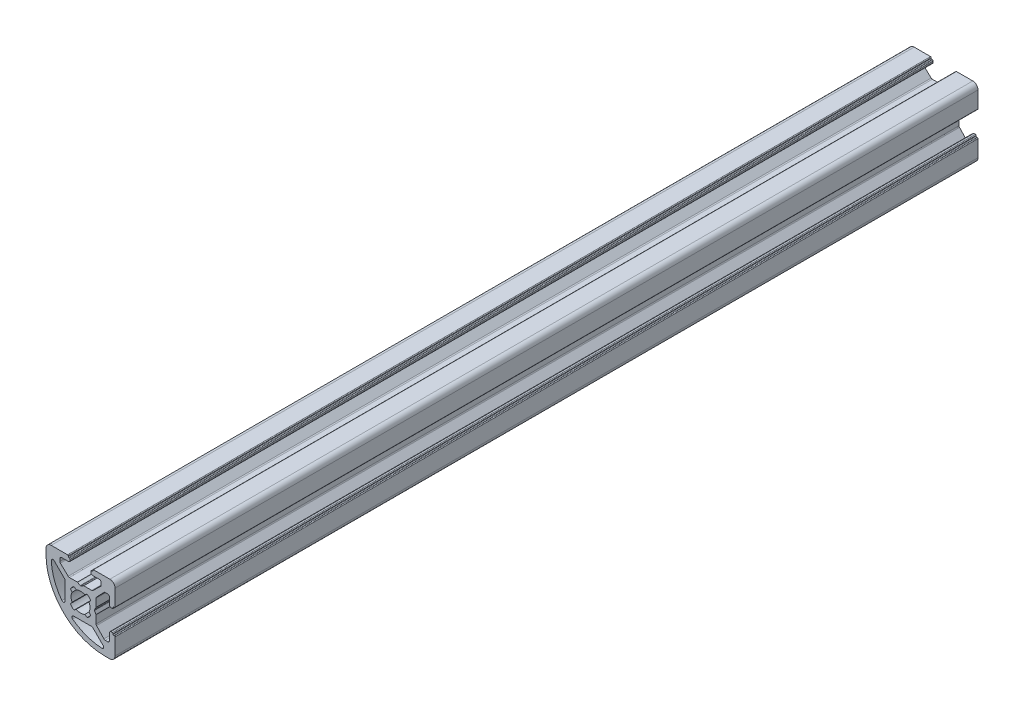
SolidWorks part; units mm, degrees
ref_plane "Front Plane" through (0, 0, 0) normal (0, 0, 1) x (1, 0, 0)
ref_plane "Top Plane" through (0, 0, 0) normal (0, 1, 0) x (1, 0, 0)
ref_plane "Right Plane" through (0, 0, 0) normal (1, 0, 0) x (0, 0, -1)
sketch "Sketch1" plane through (0, 0, 0) normal (0, 0, 1) x (1, 0, 0)
  line L0 (1.2582, 2.4453) -> (1.8871, 2.9477)
  line L1 (1.2582, -2.4453) -> (1.8871, -2.9477)
  line L2 (3.2322, 4.5654) -> (0.9536, 4.5654)
  line L3 (3.2322, -4.5) -> (-2, -4.5)
  line L4 (-1.2582, -2.4453) -> (-1.8871, -2.9477)
  line L5 (-4.6464, 3.5858) -> (-7.6257, 6.565)
  line L6 (-10, 7) -> (-10, 8.5)
  line L7 (-2.4453, -1.2582) -> (-2.9477, -1.8871)
  line L8 (-2.4453, 1.2582) -> (-2.9477, 1.8871)
  line L9 (-4.5, 3.2322) -> (-4.5, -2)
  line L10 (-1.2582, 2.4453) -> (-1.8871, 2.9477)
  line L11 (-3.2322, 4.5654) -> (-0.9536, 4.5654)
  line L12 (-3.2, 9.45) -> (-3.35, 9.45)
  line L13 (-3, 8.9321) -> (-3, 9.25)
  line L14 (-3.4918, 8.4403) -> (-5.5082, 8.4403)
  line L15 (-3.5763, 4.7027) -> (-5.8441, 6.8535)
  line L16 (-6, 7.2162) -> (-6, 7.9485)
  line L17 (-0.8536, 4.5387) -> (-0.1, 4.1036)
  line L18 (0.8536, 4.5387) -> (0.1, 4.1036)
  line L19 (-3.75, 10) -> (-8.5, 10)
  line L20 (-3.55, 9.65) -> (-3.55, 9.8)
  line L21 (4.5, -3.2322) -> (4.5, -0.9536)
  line L22 (9.65, -3.55) -> (9.8, -3.55)
  line L23 (7, -10) -> (8.5, -10)
  line L24 (4.6372, -3.5763) -> (6.788, -5.8441)
  line L25 (3.5858, -4.6464) -> (6.565, -7.6257)
  line L26 (8.3748, -3.4918) -> (8.3748, -5.5082)
  line L27 (9.45, -3.2) -> (9.45, -3.35)
  line L28 (8.8666, -3) -> (9.25, -3)
  line L29 (7.1508, -6) -> (7.883, -6)
  line L30 (10, -3.75) -> (10, -8.5)
  line L31 (9.65, 3.55) -> (9.8, 3.55)
  line L32 (8.3748, 3.4918) -> (8.3748, 5.5082)
  line L33 (4.6372, 3.5763) -> (6.788, 5.8441)
  line L34 (2.4453, 1.2582) -> (2.9477, 1.8871)
  line L35 (2.4453, -1.2582) -> (2.9477, -1.8871)
  line L36 (4.5, 3.2322) -> (4.5, 0.9536)
  line L37 (4.4732, 0.8536) -> (4.0381, 0.1)
  line L38 (4.4732, -0.8536) -> (4.0381, -0.1)
  line L39 (9.45, 3.2) -> (9.45, 3.35)
  line L40 (8.8666, 3) -> (9.25, 3)
  line L42 (3.5763, 4.7027) -> (5.8441, 6.8535)
  line L43 (3.4918, 8.4403) -> (5.5082, 8.4403)
  line L44 (3.2, 9.45) -> (3.35, 9.45)
  line L45 (3, 8.9321) -> (3, 9.25)
  line L46 (6, 7.2162) -> (6, 7.9485)
  line L47 (7.1508, 6) -> (7.883, 6)
  line L48 (10, 3.75) -> (10, 8.5)
  line L49 (3.75, 10) -> (8.5, 10)
  line L50 (3.55, 9.65) -> (3.55, 9.8)
  line L51 (0, 13.6082) -> (0, -13.4183) construction
  line L52 (-13.988, 0) -> (15.7602, 0) construction
  arc A0 (-2.3, -5.4) -> (6.1852, -8.4786) centre (7, 7) ccw
  arc A1 (-10, 7) -> (7, -10) centre (7, 7) ccw
  arc A2 (-3.55, 9.65) -> (-3.35, 9.45) centre (-3.35, 9.65) ccw
  arc A3 (-8.5, 10) -> (-10, 8.5) centre (-8.5, 8.5) ccw
  arc A4 (-5.4, -2.3) -> (-4.5, -2) centre (-5, -2) ccw
  arc A5 (-8.4786, 6.1852) -> (-5.4, -2.3) centre (7, 7) ccw
  arc A6 (-2.9477, -1.8871) -> (-1.8871, -2.9477) centre (0, 0) ccw
  arc A7 (-2, -4.5) -> (-2.3, -5.4) centre (-2, -5) ccw
  arc A8 (-1.2582, -2.4453) -> (1.2582, -2.4453) centre (0, 0) ccw
  arc A9 (-7.6257, 6.565) -> (-8.4786, 6.1852) centre (-7.9793, 6.2115) ccw
  arc A10 (-1.8871, 2.9477) -> (-2.9477, 1.8871) centre (0, 0) ccw
  arc A11 (-4.5, 3.2322) -> (-4.6464, 3.5858) centre (-5, 3.2322) ccw
  arc A12 (1.2582, 2.4453) -> (-1.2582, 2.4453) centre (0, 0) ccw
  arc A13 (-2.4453, 1.2582) -> (-2.4453, -1.2582) centre (0, 0) ccw
  arc A14 (-3, 9.25) -> (-3.2, 9.45) centre (-3.2, 9.25) ccw
  arc A15 (-3.4918, 8.4403) -> (-3, 8.9321) centre (-3.4918, 8.9321) ccw
  arc A16 (-3.5763, 4.7027) -> (-3.2322, 4.5654) centre (-3.2322, 5.0654) ccw
  arc A17 (-6, 7.2162) -> (-5.8441, 6.8535) centre (-5.5, 7.2162) ccw
  arc A18 (-5.5082, 8.4403) -> (-6, 7.9485) centre (-5.5082, 7.9485) ccw
  arc A19 (-0.1, 4.1036) -> (0.1, 4.1036) centre (0, 4.2768) ccw
  arc A20 (0.9536, 4.5654) -> (0.8536, 4.5387) centre (0.9536, 4.3654) ccw
  arc A21 (-0.8536, 4.5387) -> (-0.9536, 4.5654) centre (-0.9536, 4.3654) ccw
  arc A22 (-3.55, 9.8) -> (-3.75, 10) centre (-3.75, 9.8) ccw
  arc A23 (3.35, 9.45) -> (3.55, 9.65) centre (3.35, 9.65) ccw
  arc A24 (10, 8.5) -> (8.5, 10) centre (8.5, 8.5) ccw
  arc A25 (1.8871, -2.9477) -> (2.9477, -1.8871) centre (0, 0) ccw
  arc A26 (8.5, -10) -> (10, -8.5) centre (8.5, -8.5) ccw
  arc A27 (6.1852, -8.4786) -> (6.565, -7.6257) centre (6.2115, -7.9793) ccw
  arc A28 (4.5, -3.2322) -> (4.6372, -3.5763) centre (5, -3.2322) ccw
  arc A29 (3.5858, -4.6464) -> (3.2322, -4.5) centre (3.2322, -5) ccw
  arc A30 (9.45, -3.2) -> (9.25, -3) centre (9.25, -3.2) ccw
  arc A31 (9.45, -3.35) -> (9.65, -3.55) centre (9.65, -3.35) ccw
  arc A32 (8.8666, -3) -> (8.3748, -3.4918) centre (8.8666, -3.4918) ccw
  arc A33 (6.788, -5.8441) -> (7.1508, -6) centre (7.1508, -5.5) ccw
  arc A34 (7.883, -6) -> (8.3748, -5.5082) centre (7.883, -5.5082) ccw
  arc A35 (10, -3.75) -> (9.8, -3.55) centre (9.8, -3.75) ccw
  arc A36 (2.4453, -1.2582) -> (2.4453, 1.2582) centre (0, 0) ccw
  arc A37 (2.9477, 1.8871) -> (1.8871, 2.9477) centre (0, 0) ccw
  arc A38 (4.0381, 0.1) -> (4.0381, -0.1) centre (4.2113, 0) ccw
  arc A39 (4.5, -0.9536) -> (4.4732, -0.8536) centre (4.3, -0.9536) ccw
  arc A40 (4.4732, 0.8536) -> (4.5, 0.9536) centre (4.3, 0.9536) ccw
  arc A41 (4.6372, 3.5763) -> (4.5, 3.2322) centre (5, 3.2322) ccw
  arc A42 (9.65, 3.55) -> (9.45, 3.35) centre (9.65, 3.35) ccw
  arc A43 (9.25, 3) -> (9.45, 3.2) centre (9.25, 3.2) ccw
  arc A44 (8.3748, 3.4918) -> (8.8666, 3) centre (8.8666, 3.4918) ccw
  arc A45 (6, 7.9485) -> (5.5082, 8.4403) centre (5.5082, 7.9485) ccw
  arc A46 (3.2, 9.45) -> (3, 9.25) centre (3.2, 9.25) ccw
  arc A47 (3, 8.9321) -> (3.4918, 8.4403) centre (3.4918, 8.9321) ccw
  arc A48 (3.2322, 4.5654) -> (3.5763, 4.7027) centre (3.2322, 5.0654) ccw
  arc A49 (5.8441, 6.8535) -> (6, 7.2162) centre (5.5, 7.2162) ccw
  arc A50 (7.1508, 6) -> (6.788, 5.8441) centre (7.1508, 5.5) ccw
  arc A51 (8.3748, 5.5082) -> (7.883, 6) centre (7.883, 5.5082) ccw
  arc A52 (9.8, 3.55) -> (10, 3.75) centre (9.8, 3.75) ccw
  arc A53 (3.75, 10) -> (3.55, 9.8) centre (3.75, 9.8) ccw
  dimension "D1" = 5.5
  dimension "D5" = 17
  dimension "D7" = 5.5
  dimension "D8" = 12
  dimension "D2" = 20
  dimension "D3" = 20
  dimension "D4" = 10
  dimension "D6" = 6
  dimension "D9" = 12
extrude "Extrude1" add sketch "Sketch1" along normal blind 250
